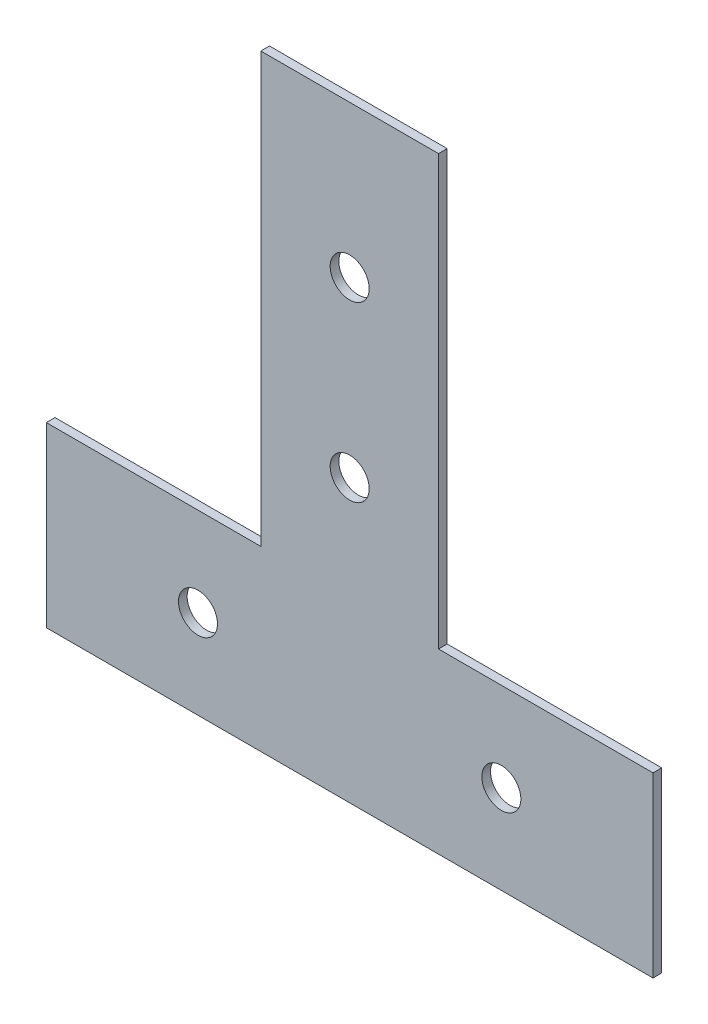
SolidWorks part; units mm, degrees
ref_plane "前视基准面" through (0, 0, 0) normal (0, 0, 1) x (1, 0, 0)
ref_plane "上视基准面" through (0, 0, 0) normal (0, 1, 0) x (1, 0, 0)
ref_plane "右视基准面" through (0, 0, 0) normal (1, 0, 0) x (0, 0, -1)
sketch "草图1" plane through (0, 0, 0) normal (0, 0, 1) x (1, 0, 0)
  line L1 (-70, -20.5) -> (70, -20.5)
  line L2 (-70, -20.5) -> (-70, 20.5)
  line L3 (-70, 20.5) -> (-20.5, 20.5)
  line L4 (70, -20.5) -> (70, 20.5)
  line L5 (-70, -20.5) -> (70, 20.5) construction
  line L6 (-70, 20.5) -> (70, -20.5) construction
  line L9 (-20.5, 119.5) -> (20.5, 119.5)
  line L10 (20.5, 20.5) -> (70, 20.5)
  line L11 (-20.5, 20.5) -> (-20.5, 119.5)
  line L12 (20.5, 20.5) -> (20.5, 119.5)
  point P0 (0, 0)
  point P6 (0, 119.5)
  dimension "D1" = 41
  dimension "D2" = 140
  dimension "D3" = 41
  dimension "D4" = 140
extrude "凸台-拉伸1" add sketch "草图1" along normal blind 2
sketch "草图2" plane through (0, 0, 2) normal (0, 0, 1) x (1, 0, 0)
  line L0 (0, 0) -> (0, 16.8919) construction
  line L2 (-70, 20.5) -> (-70, -20.5) construction
  line L3 (20.5, 119.5) -> (-20.5, 119.5) construction
  circle A0 centre (0, 84.5) radius 4.5
  circle A1 centre (0, 44.5) radius 4.5
  circle A2 centre (-35, 0) radius 4.5
  circle A3 centre (35, 0) radius 4.5
  dimension "D1" = 9
  dimension "D2" = 9
  dimension "D3" = 9
  dimension "D4" = 35
  dimension "D5" = 40
  dimension "D6" = 35
extrude "切除-拉伸1" cut sketch "草图2" against normal through all
